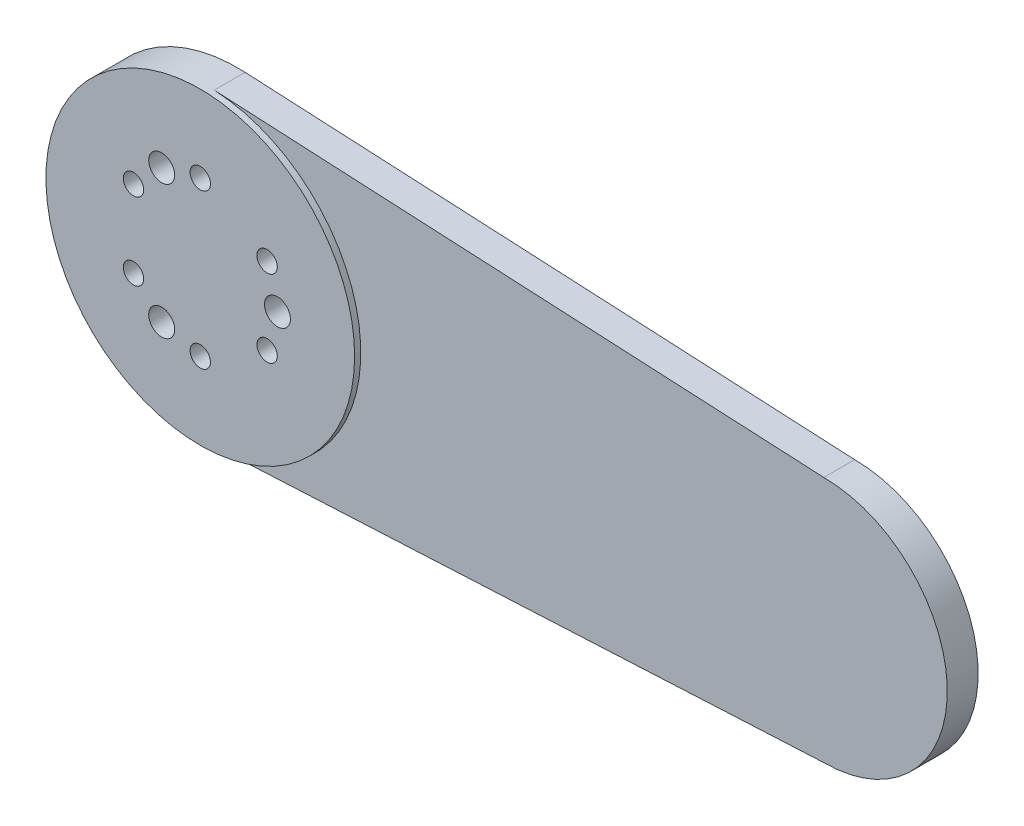
SolidWorks part; units mm, degrees
ref_plane "前视基准面" through (0, 0, 0) normal (0, 0, 1) x (1, 0, 0)
ref_plane "上视基准面" through (0, 0, 0) normal (0, 1, 0) x (1, 0, 0)
ref_plane "右视基准面" through (0, 0, 0) normal (1, 0, 0) x (0, 0, -1)
sketch "草图1" plane through (0, 0, 0) normal (0, 0, 1) x (1, 0, 0)
  line L0 (100, 20) -> (1.2563, 24.9684)
  line L1 (100, -20) -> (1.2563, -24.9684)
  circle A0 centre (0, 0) radius 12.5 construction
  arc A1 (100, -20) -> (100, 20) centre (100, 0) ccw
  arc A2 (1.2563, 24.9684) -> (1.2563, -24.9684) centre (0, 0) ccw
  circle A3 centre (0, 12.5) radius 1.65
  circle A4 centre (10.8253, 6.25) radius 1.65
  circle A5 centre (10.8253, -6.25) radius 1.65
  circle A6 centre (0, -12.5) radius 1.65
  circle A7 centre (-10.8253, -6.25) radius 1.65
  circle A8 centre (-10.8253, 6.25) radius 1.65
  circle A9 centre (12.5, 0) radius 2.1
  circle A10 centre (-6.25, -10.8253) radius 2.1
  circle A11 centre (-6.25, 10.8253) radius 2.1
  point P20 (0, 0)
  point P27 (0, 0)
  dimension "D2" = 50
  dimension "D3" = 25
  dimension "D4" = 3.3
  dimension "D6" = 4.2
  dimension "D8" = 40
  dimension "D1" = 100
  dimension "D5" = 6
  dimension "D7" = 3
extrude "凸台-拉伸1" add sketch "草图1" along normal blind 3
sketch "草图2" plane through (0, 0, 3) normal (0, 0, 1) x (1, 0, 0)
  line L0 (0, -25) -> (16.4414, -41.3415)
  line L1 (16.4414, -41.3415) -> (118.3262, -37.8789)
  line L2 (118.3262, -37.8789) -> (135.7442, 2.2035)
  line L3 (135.7442, 2.2035) -> (127.0352, 31.0586)
  line L4 (127.0352, 31.0586) -> (19.5892, 36.0951)
  line L5 (19.5892, 36.0951) -> (0, 25)
  arc A1 (0, -25) -> (0, 25) centre (0, 0) ccw
extrude "切除-拉伸1" cut sketch "草图2" against normal blind 1
sketch "草图3" plane through (0, 0, 0) normal (0, 0, -1) x (-1, 0, 0)
  line L0 (-1.1056, 21.9722) -> (-99.9276, 16.9998)
  line L1 (-99.9276, -16.9998) -> (-1.1056, -21.9722)
  line L2 (-100, -20) -> (-1.2563, -24.9684)
  line L3 (-1.2563, 24.9684) -> (-100, 20)
  line L4 (-100, -20) -> (-1.2563, -24.9684)
  line L5 (-1.2563, 24.9684) -> (-100, 20)
  arc A0 (-99.9276, 16.9998) -> (-99.9276, -16.9998) centre (-100, 0) ccw
  arc A1 (-1.1056, -21.9722) -> (-1.1056, 21.9722) centre (0, 0) ccw
  arc A2 (-100, 20) -> (-100, -20) centre (-100, 0) ccw
  arc A3 (-1.2563, -24.9684) -> (-1.2563, 24.9684) centre (0, 0) ccw
  arc A4 (-100, 20) -> (-100, -20) centre (-100, 0) ccw
  arc A5 (-1.2563, -24.9684) -> (-1.2563, 24.9684) centre (0, 0) ccw
  circle M13 centre (0, 12.5) radius 1.65
  circle M14 centre (-12.5, 0) radius 2.1
  circle M15 centre (-10.8253, 6.25) radius 1.65
  circle M16 centre (-10.8253, -6.25) radius 1.65
  circle M17 centre (0, -12.5) radius 1.65
  circle M18 centre (10.8253, -6.25) radius 1.65
  circle M19 centre (10.8253, 6.25) radius 1.65
  circle M20 centre (6.25, -10.8253) radius 2.1
  circle M21 centre (6.25, 10.8253) radius 2.1
  dimension "D1" = 0
  dimension "D2" = 3
extrude "凸台-拉伸2" add sketch "草图3" along normal blind 3 contours L1 A1 L0 A0 M14 M16 M18 M20 M21 M19 M17 M15 M13 | A4 L4 A5 L5
